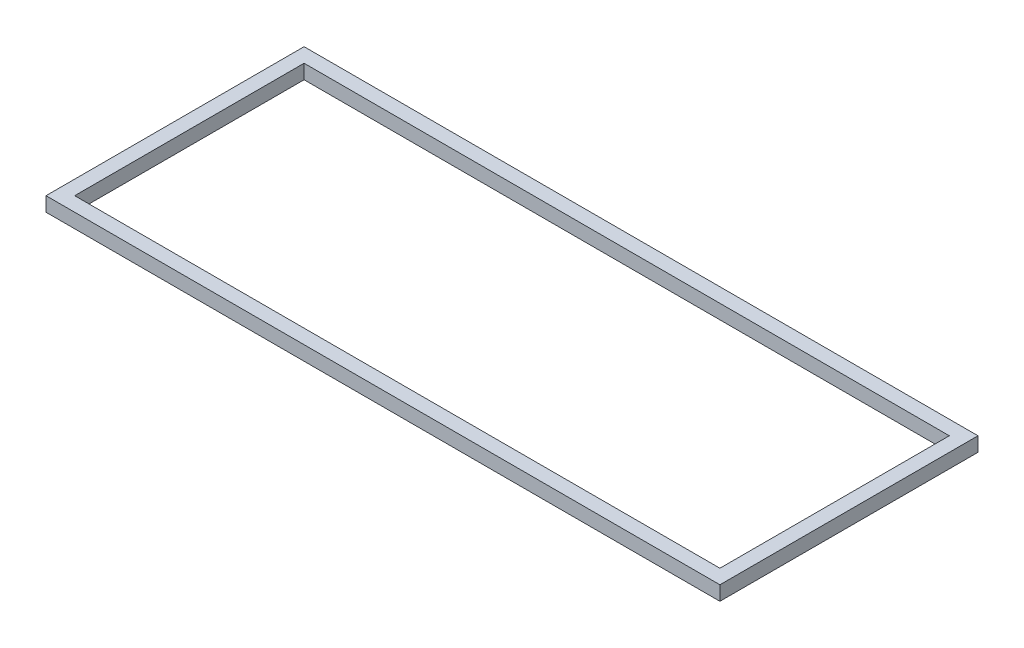
SolidWorks part; units mm, degrees
material "1060-H12"
ref_plane "Front Plane" through (0, 0, 0) normal (0, 0, 1) x (1, 0, 0)
ref_plane "Top Plane" through (0, 0, 0) normal (0, 1, 0) x (1, 0, 0)
ref_plane "Right Plane" through (0, 0, 0) normal (1, 0, 0) x (0, 0, -1)
sketch "Sketch1" plane through (0, 0, 0) normal (0, 1, 0) x (1, 0, 0)
  line L0 (-10, 10) -> (460, 10)
  line L1 (0, 0) -> (450, 0)
  line L2 (0, 0) -> (0, -160)
  line L3 (0, -160) -> (450, -160)
  line L4 (450, 0) -> (450, -160)
  line L5 (460, 10) -> (460, -170)
  line L6 (-10, -170) -> (460, -170)
  line L7 (-10, 10) -> (-10, -170)
  dimension "D1" = 160
  dimension "D2" = 450
  dimension "D3" = 10
extrude "Boss-Extrude1" add sketch "Sketch1" along normal blind 10
